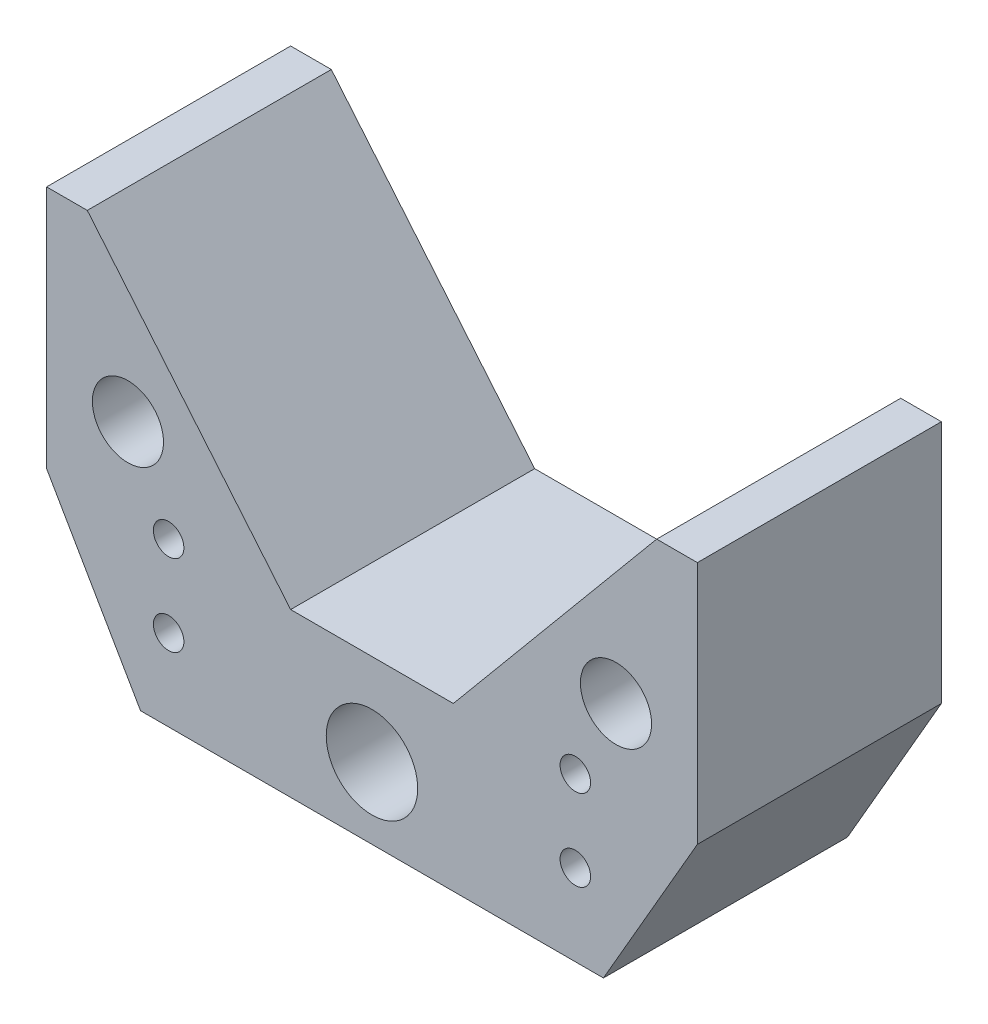
SolidWorks part; units mm, degrees
ref_plane "Front Plane" through (0, 0, 0) normal (0, 0, 1) x (1, 0, 0)
ref_plane "Top Plane" through (0, 0, 0) normal (0, 1, 0) x (1, 0, 0)
ref_plane "Right Plane" through (0, 0, 0) normal (1, 0, 0) x (0, 0, -1)
sketch "Sketch2" plane through (0, 0, 0) normal (0, 0, 1) x (1, 0, 0)
  line L0 (-72.6094, 38.8979) -> (-59.9094, 38.8979)
  line L3 (-59.9094, 38.8979) -> (3.5906, -37.3021)
  line L4 (3.5906, -37.3021) -> (28.9906, -37.3021)
  line L5 (-72.6094, -37.3021) -> (-43.28, -88.1021)
  line L6 (-43.28, -88.1021) -> (101.2612, -88.1021)
  line L8 (-72.6094, 38.8979) -> (-72.6094, -37.3021)
  line L9 (54.3906, -37.3021) -> (28.9906, -37.3021)
  line L10 (130.5906, -37.3021) -> (101.2612, -88.1021)
  line L11 (130.5906, 38.8979) -> (130.5906, -37.3021)
  line L12 (130.5906, 38.8979) -> (117.8906, 38.8979)
  line L13 (117.8906, 38.8979) -> (54.3906, -37.3021)
  circle A0 centre (-47.2094, -11.9021) radius 11.1125
  circle A1 centre (-34.5094, -37.2905) radius 4.7625
  circle A2 centre (-34.5094, -62.6905) radius 4.7625
  circle A3 centre (28.9906, -65.8771) radius 14.2875
  circle A4 centre (92.4906, -37.2905) radius 4.7625
  circle A5 centre (92.4906, -62.6905) radius 4.7625
  circle A6 centre (105.1906, -11.9021) radius 11.1125
  point P6 (16.2906, -37.3021)
  point P8 (16.2906, -37.3021)
  point P17 (28.9906, -37.3021)
  point P26 (28.9906, -88.1021)
  dimension "D1" = 120
  dimension "D4" = 28.575
  dimension "D2" = 50.8
  dimension "D3" = 72.2706
extrude "Boss-Extrude1" add sketch "Sketch2" along normal blind 76.2 contours L0 L3 L4 L9 L13 L12 L11 L10 L6 L5 L8 | A0 | A1 | A2 | A3 | A5 | A4 | A6
